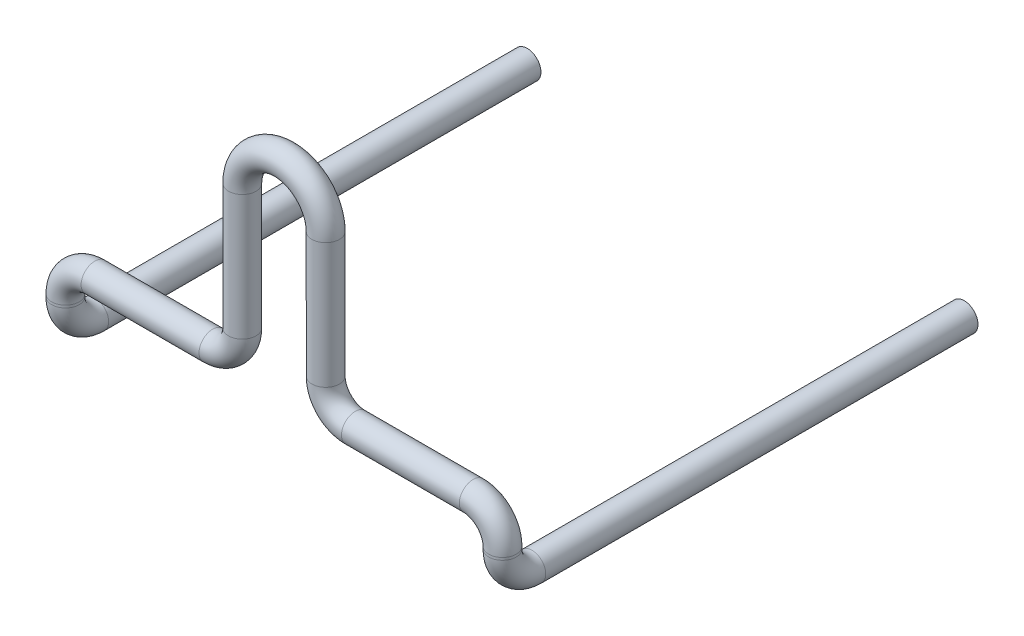
SolidWorks part; units mm, degrees
ref_plane "前视基准面" through (0, 0, 0) normal (0, 0, 1) x (1, 0, 0)
ref_plane "上视基准面" through (0, 0, 0) normal (0, 1, 0) x (1, 0, 0)
ref_plane "右视基准面" through (0, 0, 0) normal (1, 0, 0) x (0, 0, -1)
sketch "草图1" plane through (0, 0, 0) normal (0, 0, 1) x (1, 0, 0)
  line L0 (0, 0) -> (21.1, 0) construction
  line L2 (19.25, 6.25) -> (7.25, 6.25)
  line L3 (4.25, 9.25) -> (4.25, 22)
  line L4 (0, 0) -> (0, 8.8624) construction
  arc A1 (4.25, 22) -> (0, 26.25) centre (0, 22) ccw
  arc A2 (7.25, 6.25) -> (4.25, 9.25) centre (7.25, 9.25) cw
  arc A3 (22.25, 3.25) -> (19.25, 6.25) centre (19.25, 3.25) ccw
  dimension "D6" = 3
  dimension "D7" = 3
  dimension "D1" = 22.25
  dimension "D3" = 4.25
  dimension "D4" = 12.5
  dimension "D5" = 20
ref_plane "基准面2" through (22.25, 0, 0) normal (1, 0, 0) x (0, 0, -1)
sketch "草图5" plane through (22.25, 0, 0) normal (1, 0, 0) x (0, 0, -1)
  line L0 (0, -200000) -> (0, 200008.8624) construction
  line L1 (0, 3) -> (0, 3.25)
  line L2 (3, 0) -> (47, 0)
  arc A0 (3, 0) -> (0, 3) centre (3, 3) cw
  point P8 (0, 0)
  dimension "D1" = 3
  dimension "D2" = 47
sketch "草图6" plane through (0, 0, 0) normal (1, 0, 0) x (0, 0, -1)
  line L0 (0, -200000) -> (0, 200008.8624) construction
  circle A0 centre (0, 26.2457) radius 1.4
  dimension "D1" = 2.8
curve "组合曲线3"
sweep "扫描2" add profiles "草图6" path "组合曲线3"
mirror "镜向1" about plane through (0, 0, 0) normal (1, 0, 0) of "扫描2"
